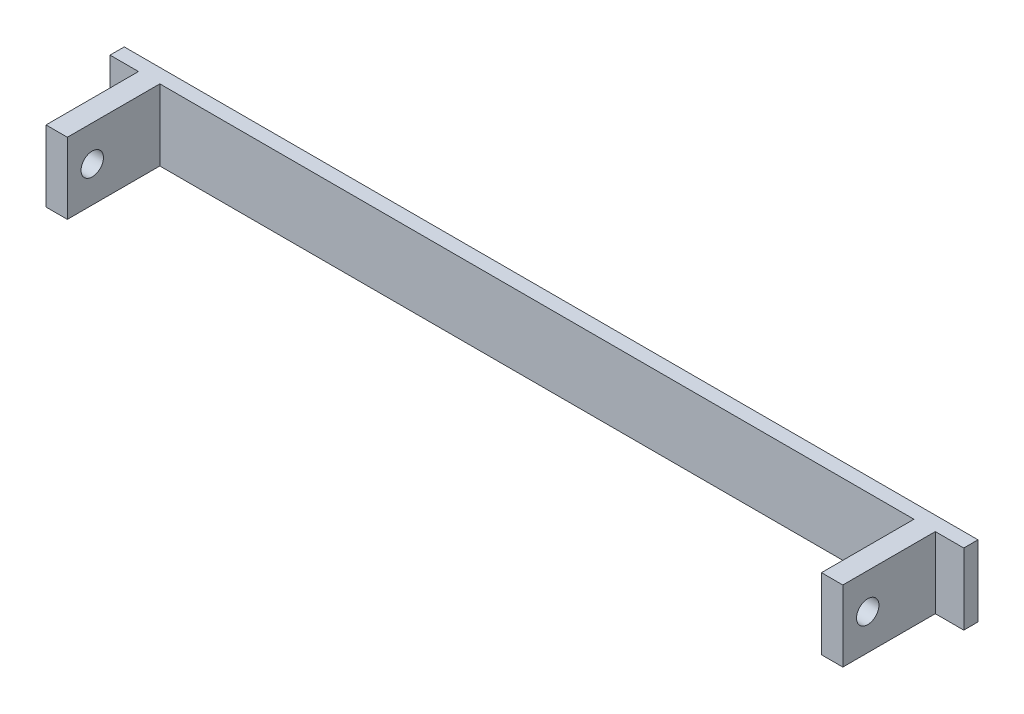
SolidWorks part; units mm, degrees
ref_plane "前视基准面" through (0, 0, 0) normal (0, 0, 1) x (1, 0, 0)
ref_plane "上视基准面" through (0, 0, 0) normal (0, 1, 0) x (1, 0, 0)
ref_plane "右视基准面" through (0, 0, 0) normal (1, 0, 0) x (0, 0, -1)
sketch "草图1" plane through (0, 0, 0) normal (0, 0, 1) x (1, 0, 0)
  line L1 (-60, -5) -> (60, -5)
  line L2 (-60, -5) -> (-60, 5)
  line L3 (-60, 5) -> (60, 5)
  line L4 (60, -5) -> (60, 5)
  line L5 (-60, -5) -> (60, 5) construction
  line L6 (-60, 5) -> (60, -5) construction
  point P0 (0, 0)
  dimension "D1" = 10
  dimension "D2" = 120
extrude "凸台-拉伸1" add sketch "草图1" along normal blind 2
sketch "草图2" plane through (0, 0, 2) normal (0, 0, 1) x (1, 0, 0)
  line L0 (60, 5) -> (-60, 5) construction
  line L1 (-56, 5) -> (-53, 5)
  line L2 (-56, 5) -> (-56, -5)
  line L3 (-56, -5) -> (-53, -5)
  line L4 (-53, 5) -> (-53, -5)
  line L5 (-60, -5) -> (60, -5) construction
  line L6 (60, -5) -> (60, 5) construction
  line L7 (53, 5) -> (56, 5)
  line L8 (53, 5) -> (53, -5)
  line L9 (53, -5) -> (56, -5)
  line L10 (56, 5) -> (56, -5)
  line L11 (-60, 5) -> (-60, -5) construction
  dimension "D1" = 3
  dimension "D2" = 4
  dimension "D3" = 3
  dimension "D4" = 4
extrude "凸台-拉伸2" add sketch "草图2" along normal blind 13
sketch "草图3" plane through (56, 0, 0) normal (1, 0, 0) x (0, 0, -1)
  line L2 (-15, 0) -> (-9.2904, 0) construction
  line L3 (-15, -5) -> (-15, 5) construction
  line L4 (0, -5) -> (0, 5) construction
  circle A0 centre (-11.5, 0) radius 1.575
  dimension "D1" = 3.15
  dimension "D2" = 11.5
extrude "切除-拉伸1" cut sketch "草图3" against normal up to surface (112 mm away) up to face at (-56, 0, 8.5)
